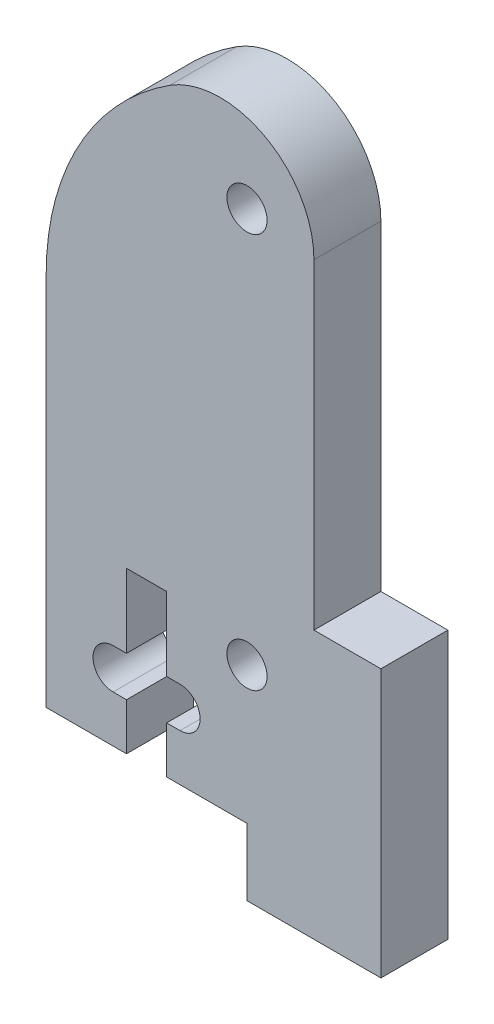
SolidWorks part; units mm, degrees
ref_plane "Front Plane" through (0, 0, 0) normal (0, 0, 1) x (1, 0, 0)
ref_plane "Top Plane" through (0, 0, 0) normal (0, 1, 0) x (1, 0, 0)
ref_plane "Right Plane" through (0, 0, 0) normal (1, 0, 0) x (0, 0, -1)
sketch "Sketch1" plane through (0, 0, 0) normal (0, 0, 1) x (1, 0, 0)
  line L1 (8.6003, -27.3594) -> (-11.3997, -27.3594)
  line L2 (8.6003, -12.3594) -> (8.6003, 20.6406)
  line L3 (8.6003, -27.3594) -> (13.6003, -27.3594)
  line L4 (-11.3997, -27.3594) -> (-11.3997, 0.6406)
  line L5 (8.6003, -27.3594) -> (-9.2954, 29.5707) construction
  line L6 (8.6003, 20.6406) -> (-11.3997, -27.3594) construction
  line L8 (8.6003, -12.3594) -> (13.6003, -12.3594)
  line L9 (13.6003, -27.3594) -> (13.6003, -12.3594)
  line L17 (13.6003, -27.3594) -> (3.6003, -27.3594)
  line L18 (13.6003, -27.3594) -> (13.6003, -32.3594)
  line L19 (13.6003, -32.3594) -> (3.6003, -32.3594)
  line L20 (3.6003, -27.3594) -> (3.6003, -32.3594)
  arc A0 (8.6003, 20.6406) -> (-11.3997, 0.6406) centre (8.6003, 0.6406) ccw
  point P0 (0, 0)
  dimension "D1" = 20
  dimension "D2" = 48
  dimension "D3" = 5
  dimension "D4" = 15
  dimension "D8" = 5
  dimension "D9" = 10
  dimension "D10" = 20
  dimension "D11" = 5
extrude "Boss-Extrude1" add sketch "Sketch1" along normal blind 5
sketch "Sketch2" plane through (0, 0, 5) normal (0, 0, 1) x (1, 0, 0)
  line L0 (3.6003, -27.3594) -> (-11.3997, -27.3594) construction
  line L1 (-2.3997, -27.3594) -> (-5.3997, -27.3594)
  line L2 (-2.3997, -27.3594) -> (-2.3997, -15.3594)
  line L3 (-2.3997, -15.3594) -> (-5.3997, -15.3594)
  line L4 (-5.3997, -27.3594) -> (-5.3997, -15.3594)
  line L5 (-6.3997, -22.3594) -> (-1.3997, -22.3594) construction
  line L6 (-6.3997, -20.8594) -> (-1.3997, -20.8594)
  line L7 (-6.3997, -23.8594) -> (-1.3997, -23.8594)
  line L8 (-3.8997, -15.3594) -> (-3.8997, -22.3594) construction
  line L9 (-3.8997, -27.3594) -> (-3.8997, -22.3594) construction
  arc A0 (-6.3997, -20.8594) -> (-6.3997, -23.8594) centre (-6.3997, -22.3594) ccw
  arc A1 (-1.3997, -23.8594) -> (-1.3997, -20.8594) centre (-1.3997, -22.3594) ccw
  point P8 (-3.8997, -22.3594)
  dimension "D1" = 3
  dimension "D2" = 8
  dimension "D3" = 3
  dimension "D4" = 12
  dimension "D5" = 5
extrude "Cut-Extrude1" cut sketch "Sketch2" against normal blind 10 contours L6 A1 L7 A0 | L2 L3 L4 L1
fillet "Fillet1" radius 7 1 edges at (8.6003, 20.6406, 2.5)
sketch "Sketch3" plane through (0, 0, 5) normal (0, 0, 1) x (1, 0, 0)
  line L0 (3.6003, 12.3906) -> (3.6003, -17.1094) construction
  line L1 (8.6003, -12.3594) -> (8.6003, 11.5951) construction
  line L2 (3.6003, -2.3594) -> (8.6003, -2.3594) construction
  line L3 (13.6003, -32.3594) -> (3.6003, -32.3594) construction
  circle A0 centre (3.6003, -17.1094) radius 1.5
  circle A1 centre (3.6003, 12.3906) radius 1.5
  dimension "D1" = 3
  dimension "D2" = 5
  dimension "D3" = 30
  dimension "D4" = 29.5
extrude "Cut-Extrude2" cut sketch "Sketch3" against normal blind 10
